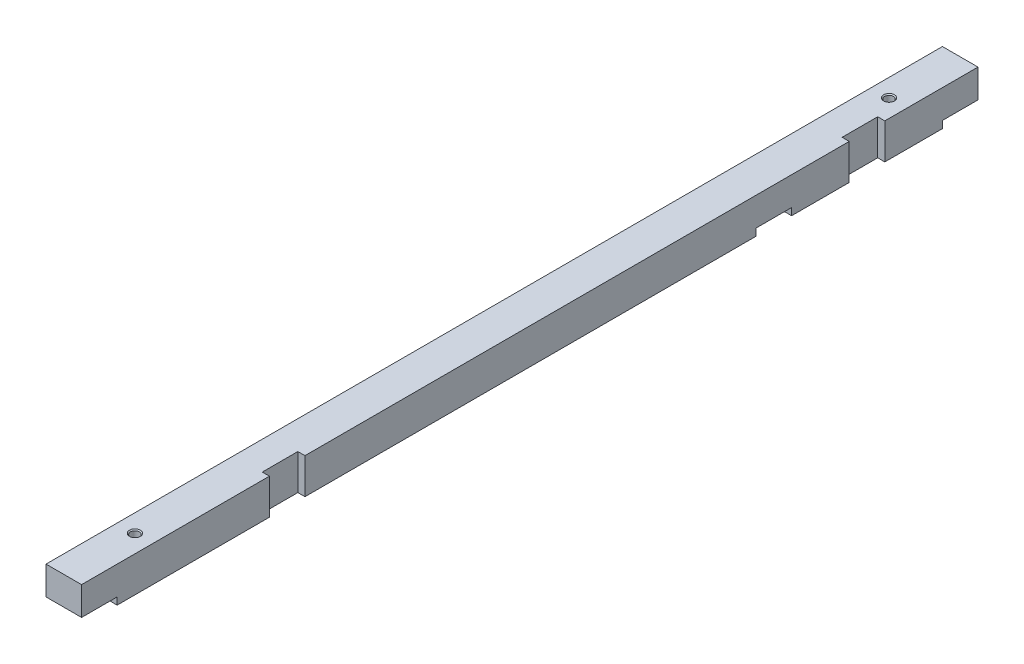
SolidWorks part; units mm, degrees
ref_plane "Plan de face" through (0, 0, 0) normal (0, 0, 1) x (1, 0, 0)
ref_plane "Plan de dessus" through (0, 0, 0) normal (0, 1, 0) x (1, 0, 0)
ref_plane "Plan de droite" through (0, 0, 0) normal (1, 0, 0) x (0, 0, -1)
sketch "Esquisse1" plane through (0, 0, 0) normal (0, 0, 1) x (1, 0, 0)
  line L0 (-5, 5) -> (5, -5) construction
  line L1 (-5, 5) -> (5, 5)
  line L2 (-5, 5) -> (-5, -5)
  line L3 (-5, -5) -> (5, -5)
  line L4 (5, 5) -> (5, -5)
  dimension "D1" = 10
extrude "Boss.-Extru.1" add sketch "Esquisse1" along normal blind 252
sketch "Esquisse2" plane through (-5, 0, 0) normal (-1, 0, 0) x (0, 0, 1)
  line L0 (0, -3) -> (0, -303) construction
  line L1 (0, -5) -> (10, -5)
  line L2 (0, -5) -> (0, -3)
  line L3 (0, -3) -> (10, -3)
  line L4 (10, -5) -> (10, -3)
  line L5 (10, -3) -> (10, -170) construction
  line L6 (52.4, -3) -> (52.4, -170) construction
  line L7 (52.4, -5) -> (62.4, -5)
  line L8 (52.4, -5) -> (52.4, -3)
  line L9 (52.4, -3) -> (62.4, -3)
  line L10 (62.4, -5) -> (62.4, -3)
  line L11 (62.4, -3) -> (62.4, -170) construction
  line L12 (242, -3) -> (242, -170) construction
  line L13 (242, -5) -> (252, -5)
  line L14 (242, -5) -> (242, -3)
  line L15 (242, -3) -> (252, -3)
  line L16 (252, -5) -> (252, -3)
  line L17 (252, -3) -> (252, -297.8) construction
  line L18 (252, -5) -> (0, -5) construction
  dimension "D1" = 2
extrude "Enlèv. mat.-Extru.1" cut sketch "Esquisse2" against normal through all
sketch "Esquisse3" plane through (0, -5, 0) normal (0, -1, 0) x (1, 0, 0)
  line L4 (3, 36.2) -> (3, 26.2)
  line L5 (234, 36.2) -> (3, 36.2)
  line L6 (234, 26.2) -> (234, 36.2)
  line L7 (3, 26.2) -> (234, 26.2)
  line L8 (3, 36.2) -> (3, 26.2)
  line L9 (234, 36.2) -> (3, 36.2)
  line L10 (234, 26.2) -> (234, 36.2)
  line L11 (3, 26.2) -> (234, 26.2)
  dimension "D1" = 0
extrude "Enlèv. mat.-Extru.2" cut sketch "Esquisse3" against normal through all
sketch "Esquisse4" plane through (0, 5, 0) normal (0, 1, 0) x (1, 0, 0)
  line L4 (3, -189.2) -> (3, -199.2)
  line L5 (3, -199.2) -> (234, -199.2)
  line L6 (234, -199.2) -> (234, -189.2)
  line L7 (234, -189.2) -> (3, -189.2)
  line L8 (3, -189.2) -> (3, -199.2)
  line L9 (3, -199.2) -> (234, -199.2)
  line L10 (234, -199.2) -> (234, -189.2)
  line L11 (234, -189.2) -> (3, -189.2)
  dimension "D1" = 0
extrude "Enlèv. mat.-Extru.3" cut sketch "Esquisse4" against normal through all
sketch "Esquisse5" plane through (0, 5, 0) normal (0, 1, 0) x (1, 0, 0)
  line L0 (3, -199.2) -> (234, -199.2) construction
  line L1 (-5, -199.2) -> (-3, -199.2)
  line L2 (-5, -199.2) -> (-5, -189.2)
  line L3 (-5, -189.2) -> (-3, -189.2)
  line L4 (-3, -199.2) -> (-3, -189.2)
  line L5 (3, -189.2) -> (234, -189.2) construction
  line L6 (3, -36.2) -> (234, -36.2) construction
  line L7 (-5, -36.2) -> (-3, -36.2)
  line L8 (-5, -36.2) -> (-5, -26.2)
  line L9 (-5, -26.2) -> (-3, -26.2)
  line L10 (-3, -36.2) -> (-3, -26.2)
  line L11 (3, -26.2) -> (234, -26.2) construction
  line L12 (-5, -252) -> (-5, 0) construction
  dimension "D1" = 2
extrude "Enlèv. mat.-Extru.4" [suppressed] cut sketch "Esquisse5" against normal through all
hole_wizard "Trou taraudé M3x0.51" positions "Esquisse7" profile "Esquisse6" tap size "M3x0.5" standard "Ansi Metric" end condition through all
sketch "Esquisse7" plane through (0, 5, 0) normal (0, 1, 0) x (1, 0, 0)
  point P0 (0, -20)
  point P3 (0, -232)
sketch "Esquisse6" plane through (0, 5, 20) normal (1, 0, 0) x (0, 0, 1)
  line L0 (0, 0) -> (0, 10)
  line L1 (0, 10) -> (1.25, 10)
  line L2 (1.25, 10) -> (1.25, 0.275)
  line L3 (1.25, 0.275) -> (1.525, 0)
  line L5 (1.525, 0) -> (0, 0)
  line L6 (-1.25, 0.275) -> (-1.525, 0) construction
  line L11 (0, -6.35) -> (0, 107.95) construction
  dimension "Diamètre du trou pour taraudage jusqu'au prochain" = 2.5
  dimension "Profondeur du trou pour taraudage jusqu'au prochain" = 10
  dimension "Diamètre du fraisage entrant" = 3.05
  dimension "Angle du fraisage entrant" = 90
cosmetic thread "Filetage de perçage1" parameters "D2"=3
cosmetic thread "Filetage de perçage2" parameters "D2"=3
